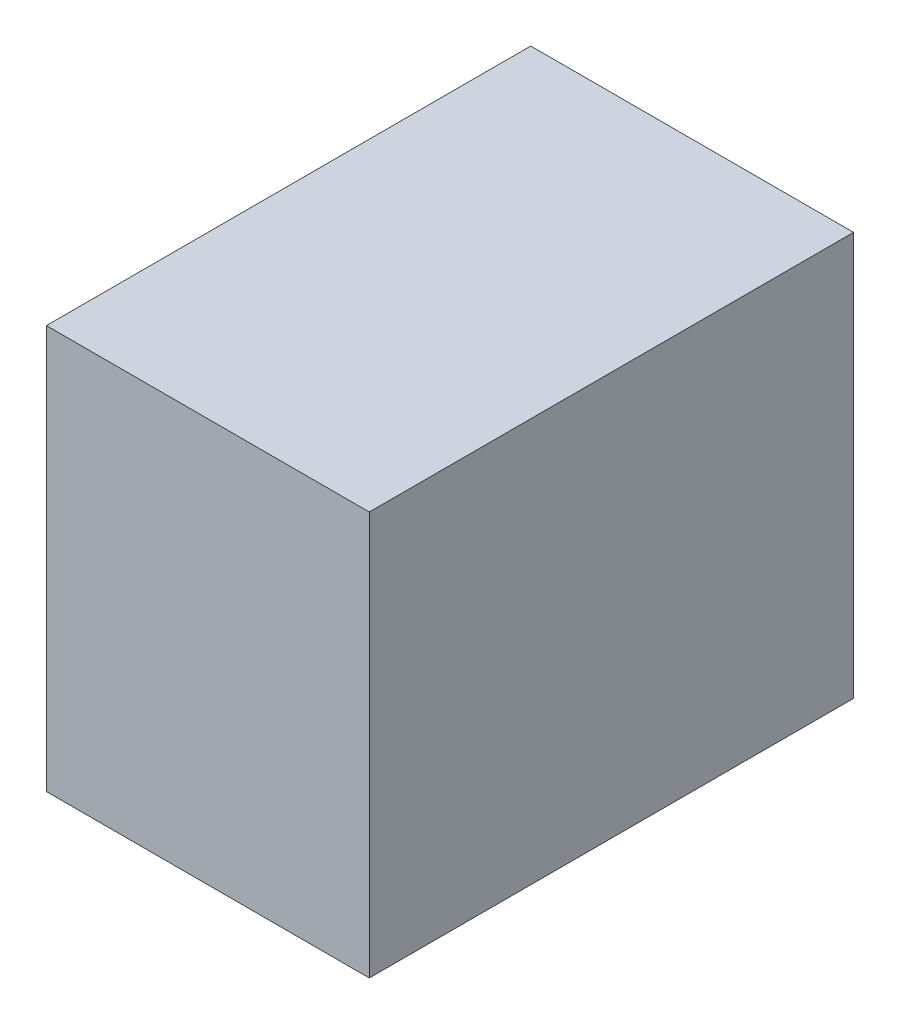
SolidWorks part; units mm, degrees
ref_plane "Front Plane" through (0, 0, 0) normal (0, 0, 1) x (1, 0, 0)
ref_plane "Top Plane" through (0, 0, 0) normal (0, 1, 0) x (1, 0, 0)
ref_plane "Right Plane" through (0, 0, 0) normal (1, 0, 0) x (0, 0, -1)
other "Configuration Table"
sketch "Sketch1" plane through (0, 0, 0) normal (0, 0, 1) x (1, 0, 0)
  line L1 (220, 320) -> (260, 320)
  line L2 (220, 320) -> (220, 370)
  line L3 (220, 370) -> (260, 370)
  line L4 (260, 320) -> (260, 370)
extrude "PACK_vakum_selenoid_taban_1" add sketch "Sketch1" against normal blind 60 from offset 620 separate body
